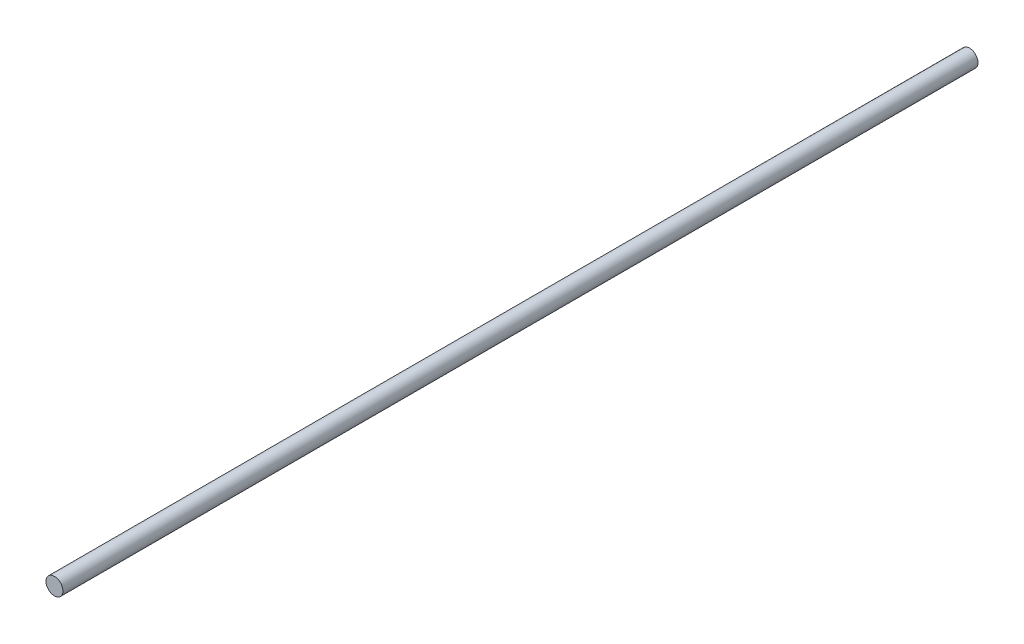
SolidWorks part; units mm, degrees
material "AISI 304"
ref_plane "Front Plane" through (0, 0, 0) normal (0, 0, 1) x (1, 0, 0)
ref_plane "Top Plane" through (0, 0, 0) normal (0, 1, 0) x (1, 0, 0)
ref_plane "Right Plane" through (0, 0, 0) normal (1, 0, 0) x (0, 0, -1)
sketch "Sketch1" plane through (0, 0, 0) normal (0, 0, 1) x (1, 0, 0)
  circle A0 centre (0, 0) radius 2
  dimension "D1" = 4
extrude "Boss-Extrude1" add sketch "Sketch1" along normal mid plane 216
